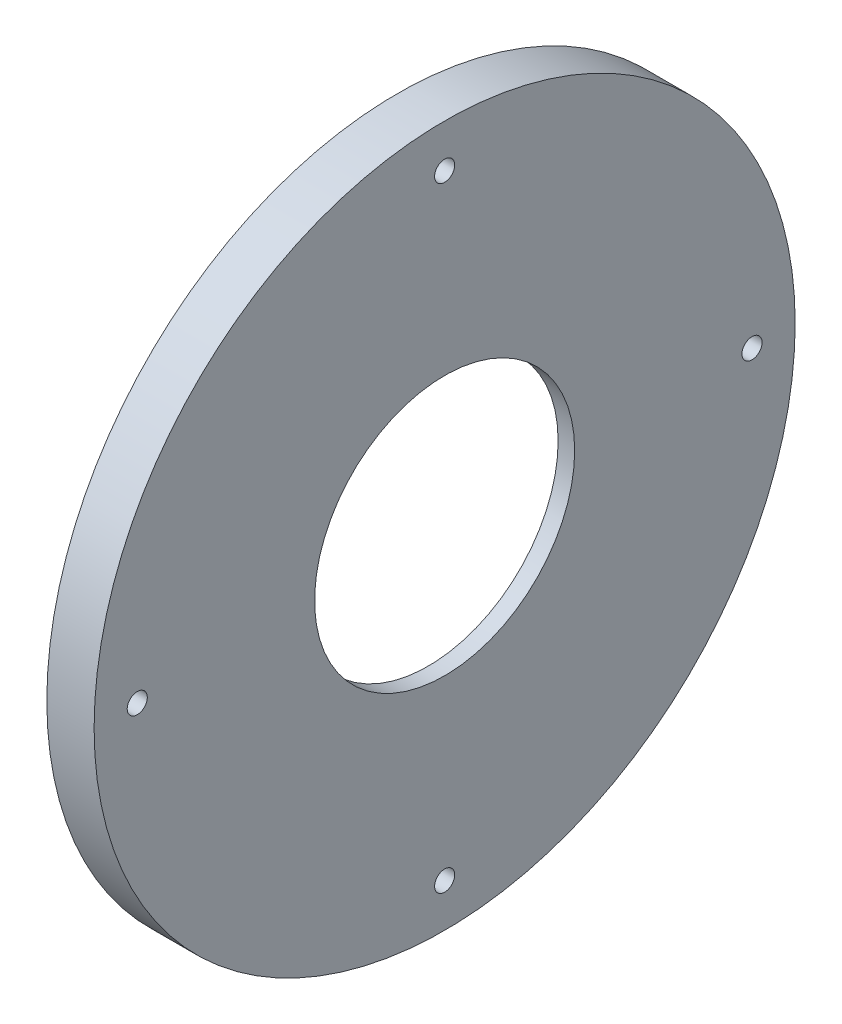
SolidWorks part; units mm, degrees
ref_plane "Plan de face" through (0, 0, 0) normal (0, 0, 1) x (1, 0, 0)
ref_plane "Plan de dessus" through (0, 0, 0) normal (0, 1, 0) x (1, 0, 0)
ref_plane "Plan de droite" through (0, 0, 0) normal (1, 0, 0) x (0, 0, -1)
sketch "Esquisse1" plane through (0, 0, 0) normal (0, 0, 1) x (1, 0, 0)
  line L0 (387.8517, 0) -> (407.8517, 0)
  line L1 (407.8517, 0) -> (407.8517, 148.25)
  line L2 (407.8517, 148.25) -> (387.8517, 148.25)
  line L3 (387.8517, 148.25) -> (387.8517, 0)
  line L4 (387.8517, 0) -> (407.8517, 0)
  line L5 (22.6724, 0) -> (506.5435, 0)
  dimension "D1" = 148.25
  dimension "D2" = 20
revolve "Révolution1" add sketch "Esquisse1" angle 360 about L5
sketch "Esquisse2" plane through (407.8517, 0, 0) normal (1, 0, 0) x (0, 0, -1)
  circle A0 centre (0, 0) radius 55
  dimension "D1" = 110
extrude "Enlèv. mat.-Extru.1" cut sketch "Esquisse2" against normal through all contours A0
sketch "Esquisse3" plane through (387.8517, 0, 0) normal (-1, 0, 0) x (0, 0, 1)
  circle A0 centre (0, 0) radius 87.6376
extrude "Enlèv. mat.-Extru.2" cut sketch "Esquisse3" against normal blind 13
sketch "Esquisse4" plane through (387.8517, 0, 0) normal (-1, 0, 0) x (0, 0, 1)
  line L0 (0, 130) -> (0, -130)
  line L1 (-130, 0) -> (130, 0)
  circle A0 centre (0, 0) radius 130
  circle A1 centre (0, 130) radius 4.984
  circle A2 centre (0, -130) radius 4.984
  circle A3 centre (0, -130) radius 4.984
  circle A4 centre (130, 0) radius 4.984
  circle A5 centre (-130, 0) radius 4.984
  point P11 (0, 0)
  dimension "D1" = 260
  dimension "D2" = 9.968
  dimension "D3" = 9.968
hole_wizard "Trou taraudé M101" positions "Esquisse3D1" profile "Esquisse5" tap size "M10" standard "ISO" end condition through all
sketch3d "Esquisse3D1"
  point P0 (387.8517, 130, 0)
  point P3 (387.8517, 0, -130)
  point P6 (387.8517, -130, 0)
  point P9 (387.8517, 0, 130)
sketch "Esquisse5" plane through (387.8517, 130, 0) normal (0, 1, 0) x (0, 0, 1)
  line L0 (0, 0) -> (0, 20)
  line L1 (0, 20) -> (4.25, 20)
  line L2 (4.25, 20) -> (4.25, 0)
  line L5 (4.25, 0) -> (0, 0)
  line L11 (0, -6.35) -> (0, 107.95) construction
  dimension "Diamètre du trou pour taraudage jusqu'au prochain" = 8.5
  dimension "Profondeur du trou pour taraudage jusqu'au prochain" = 20
cosmetic thread "Filetage de perçage1" parameters "D2"=10
cosmetic thread "Filetage de perçage2" parameters "D2"=10
cosmetic thread "Filetage de perçage3" parameters "D2"=10
cosmetic thread "Filetage de perçage4" parameters "D2"=10
